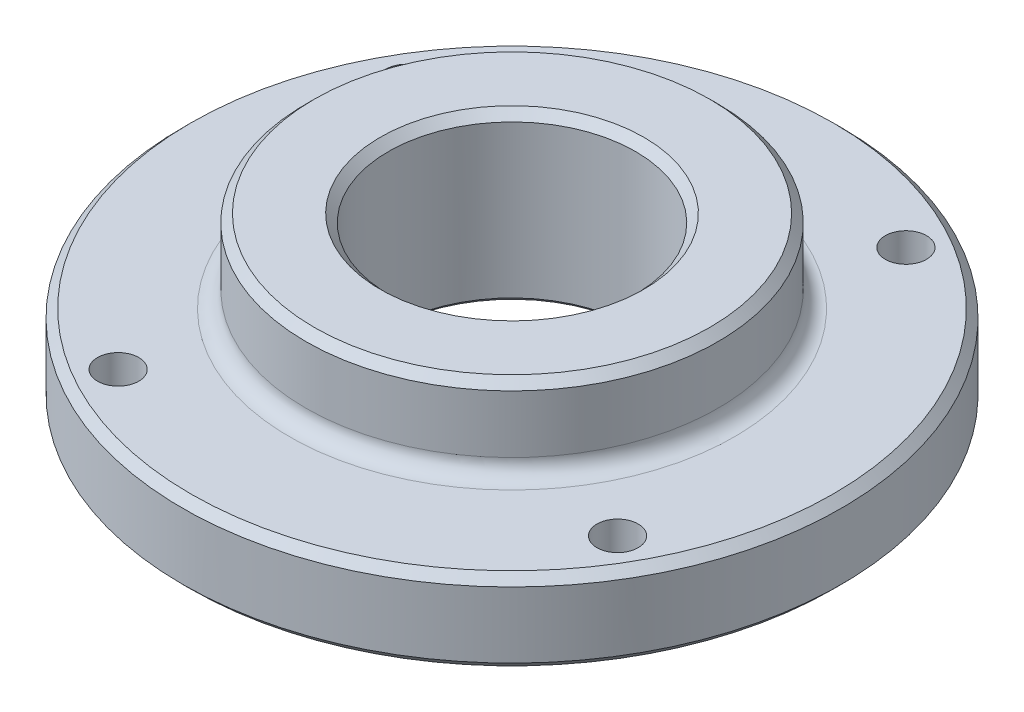
SolidWorks part; units mm, degrees
material "Cast Carbon Steel"
ref_plane "Front Plane" through (0, 0, 0) normal (0, 0, 1) x (1, 0, 0)
ref_plane "Top Plane" through (0, 0, 0) normal (0, 1, 0) x (1, 0, 0)
ref_plane "Right Plane" through (0, 0, 0) normal (1, 0, 0) x (0, 0, -1)
sketch "Sketch1" plane through (0, 0, 0) normal (0, 0, 1) x (1, 0, 0)
  line L0 (0, 0) -> (0, 20.473) construction
  line L1 (-15, 0) -> (-15, 20)
  line L2 (-15, 20) -> (-25, 20)
  line L3 (-25, 20) -> (-25, 10)
  line L4 (-25, 10) -> (-40, 10)
  line L5 (-40, 10) -> (-40, 0)
  line L6 (-40, 0) -> (-15, 0)
  dimension "D1" = 10
  dimension "D2" = 15
  dimension "D3" = 10
  dimension "D4" = 20
  dimension "D5" = 40
revolve "Revolve1" add sketch "Sketch1" angle 360 about L0
chamfer "Chamfer1" distance 1 angle 45 1 edges at (0, 20, -15)
sketch "Sketch3" plane through (0, 10, 0) normal (0, 1, 0) x (1, 0, 0)
  line L0 (0, 0) -> (0, 42.8148) construction
  line L1 (0, 0) -> (22.2435, 38.5269) construction
  circle A0 centre (0, 0) radius 35 construction
  circle A1 centre (17.5, 30.3109) radius 2.5
  circle A2 centre (30.3109, -17.5) radius 2.5
  circle A3 centre (-17.5, -30.3109) radius 2.5
  circle A4 centre (-30.3109, 17.5) radius 2.5
  point P16 (0, 0)
  dimension "D2" = 70
  dimension "D3" = 5
  dimension "D1" = 30
  dimension "D4" = 4
extrude "Cut-Extrude1" cut sketch "Sketch3" against normal up to next
fillet "Fillet1" radius 2 1 edges at (0, 10, -25)
chamfer "Chamfer2" distance 1 angle 45 3 edges at (0, 10, -40) (0, 0, -40) (0, 20, -25)
chamfer "Chamfer3" distance 0.5 angle 45 1 edges at (0, 0, -15)
